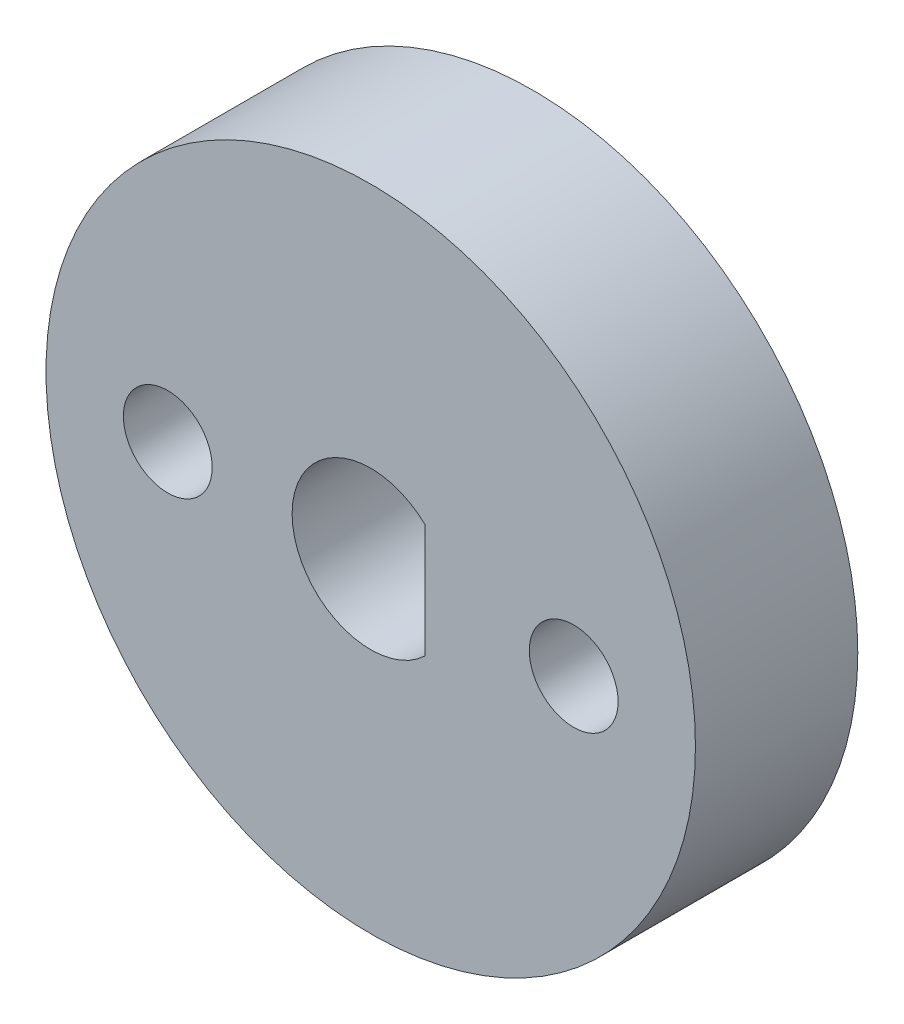
SolidWorks part; units mm, degrees
ref_plane "Front Plane" through (0, 0, 0) normal (0, 0, 1) x (1, 0, 0)
ref_plane "Top Plane" through (0, 0, 0) normal (0, 1, 0) x (1, 0, 0)
ref_plane "Right Plane" through (0, 0, 0) normal (1, 0, 0) x (0, 0, -1)
sketch "Sketch1" plane through (0, 0, 0) normal (0, 0, 1) x (1, 0, 0)
  line L0 (2.2225, 2.2674) -> (2.2225, -2.2674)
  line L1 (2.1225, 2.225) -> (2.1225, -2.225)
  arc A0 (2.2225, 2.2674) -> (2.2225, -2.2674) centre (0, 0) ccw
  circle A1 centre (0, 0) radius 12.7
  arc A2 (2.1225, 2.225) -> (2.1225, -2.225) centre (0, 0) ccw
  dimension "D1" = 6.35
  dimension "D3" = 25.4
  dimension "D2" = 2.2225
  dimension "D4" = 0.1
extrude "Boss-Extrude1" add sketch "Sketch1" along normal blind 6.35 contours A1 A0 L0 | L0 A0 A2 L1
sketch "Sketch2" plane through (0, 0, 6.35) normal (0, 0, 1) x (1, 0, 0)
  line L0 (-7.9375, 0) -> (0, 0) construction
  line L1 (0, 0) -> (7.9375, 0) construction
  circle A0 centre (7.9375, 0) radius 1.7359
  circle A1 centre (-7.9375, 0) radius 1.7359
  dimension "D2" = 3.4719
  dimension "D1" = 7.9375
extrude "Cut-Extrude1" cut sketch "Sketch2" against normal through all both and the other way through all
